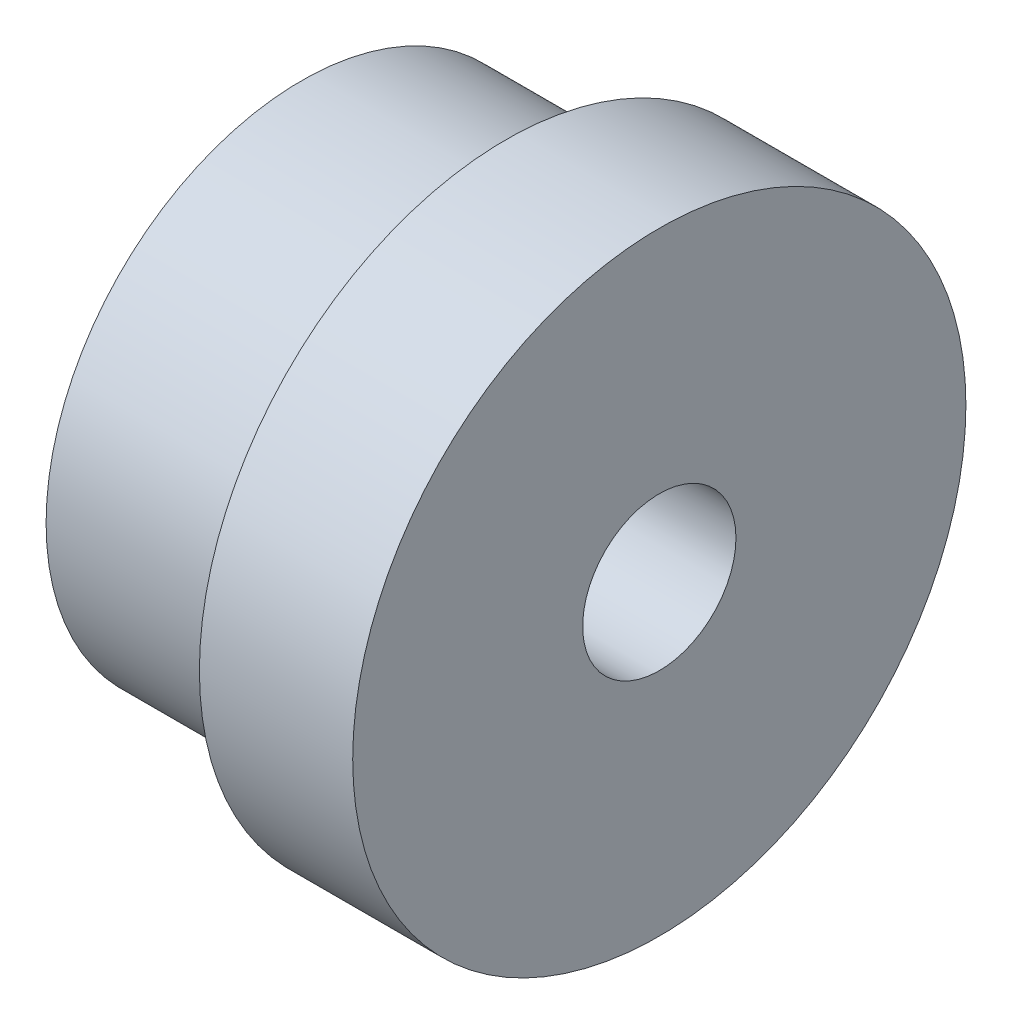
SolidWorks part; units mm, degrees
ref_plane "Front Plane" through (0, 0, 0) normal (0, 0, 1) x (1, 0, 0)
ref_plane "Top Plane" through (0, 0, 0) normal (0, 1, 0) x (1, 0, 0)
ref_plane "Right Plane" through (0, 0, 0) normal (1, 0, 0) x (0, 0, -1)
sketch "Sketch1" plane through (0, 0, 0) normal (1, 0, 0) x (0, 0, -1)
  circle A0 centre (0, 0) radius 9.525
  dimension "D1" = 19.05
extrude "Boss-Extrude1" add sketch "Sketch1" along normal blind 4.7625
sketch "Sketch2" plane through (0, 0, 0) normal (-1, 0, 0) x (0, 0, 1)
  circle A0 centre (0, 0) radius 7.9375
  dimension "D1" = 15.875
extrude "Boss-Extrude2" add sketch "Sketch2" along normal blind 6.35
hole_wizard "#4 Clearance Hole1" positions "Sketch4" profile "Sketch5" hole size "#4" standard "ANSI Inch" end condition through all
sketch "Sketch4" plane through (4.7625, 0, 0) normal (1, 0, 0) x (0, 0, -1)
  point P0 (0, 0)
sketch "Sketch5" plane through (4.7625, 0, 0) normal (0, 1, 0) x (0, 0, -1)
  line L0 (0, 0) -> (0, 11.1125)
  line L1 (0, 11.1125) -> (2.3812, 11.1125)
  line L2 (2.3812, 11.1125) -> (2.3812, 0)
  line L5 (2.3812, 0) -> (0, 0)
  line L11 (0, -6.35) -> (0, 107.95) construction
  dimension "Thru Hole Dia." = 4.7625
  dimension "Thru Hole Depth" = 11.1125
